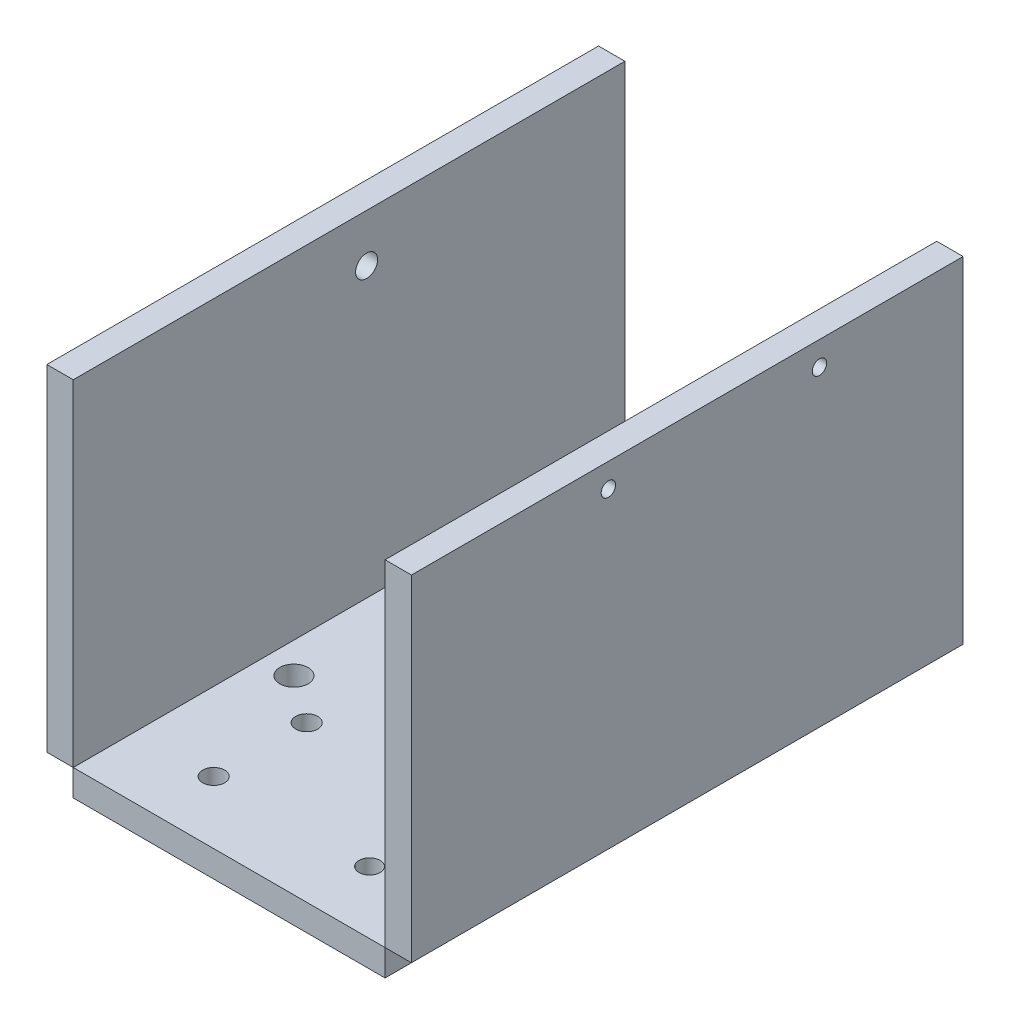
SolidWorks part; units mm, degrees
ref_plane "Alzado" through (0, 0, 0) normal (0, 0, 1) x (1, 0, 0)
ref_plane "Planta" through (0, 0, 0) normal (0, 1, 0) x (1, 0, 0)
ref_plane "Vista lateral" through (0, 0, 0) normal (1, 0, 0) x (0, 0, -1)
sketch "Croquis1" plane through (0, 0, 0) normal (0, 1, 0) x (1, 0, 0)
  line L0 (0, -12.4562) -> (32.5, -12.4562) construction
  line L1 (0, 0) -> (65, 0)
  line L2 (0, 0) -> (0, -115)
  line L3 (0, -115) -> (65, -115)
  line L4 (65, 0) -> (65, -115)
  line L5 (32.5, 0) -> (32.5, -12.4562) construction
  line L6 (32.5, -12.4562) -> (65, -12.4562) construction
  line L7 (48.75, -6.2281) -> (16.25, -6.2281) construction
  line L8 (16.25, -6.2281) -> (16.25, -12.4562) construction
  line L9 (16.25, -18.6843) -> (16.25, -82.5875) construction
  line L10 (16.25, -82.5875) -> (48.75, -82.5875) construction
  line L11 (16.25, -82.5875) -> (16.25, -92.2821) construction
  line L12 (16.25, -92.2821) -> (48.75, -92.2821) construction
  circle A0 centre (16.25, -6.2281) radius 2.3
  circle A1 centre (48.75, -6.2281) radius 2.3
  circle A2 centre (48.75, -18.6843) radius 2.3
  circle A3 centre (16.25, -18.6843) radius 2.3
  circle A4 centre (16.25, -82.5875) radius 2.3
  circle A5 centre (48.75, -82.5875) radius 2.2
  circle A6 centre (48.75, -101.9767) radius 2.2
  circle A7 centre (16.25, -101.9767) radius 2.3
  point P13 (32.5, -6.2281)
  dimension "D3" = 6.2281
  dimension "D1" = 65
  dimension "D2" = 115
extrude "Saliente-Extruir1" add sketch "Croquis1" along normal blind 5.5
sketch "Croquis2" plane through (0, 0, 0) normal (-1, 0, 0) x (0, 0, 1)
  line L1 (115, 5.5) -> (0, 5.5)
  line L2 (115, 5.5) -> (115, 75.5)
  line L3 (115, 75.5) -> (0, 75.5)
  line L4 (0, 5.5) -> (0, 75.5)
  dimension "D1" = 70
  dimension "D2" = 115
extrude "Saliente-Extruir2" add sketch "Croquis2" along normal blind 5.5 separate body
sketch "Croquis3" plane through (65, 0, 0) normal (1, 0, 0) x (0, 0, -1)
  line L1 (0, 5.5) -> (-115, 5.5)
  line L2 (0, 5.5) -> (0, 75.5)
  line L3 (0, 75.5) -> (-115, 75.5)
  line L4 (-115, 5.5) -> (-115, 75.5)
  dimension "D1" = 70
  dimension "D2" = 115
extrude "Saliente-Extruir3" add sketch "Croquis3" along normal blind 5.5 separate body
sketch "Croquis4" plane through (0, 5.5, 0) normal (0, 1, 0) x (1, 0, 0)
  circle A0 centre (55.6386, -75.4209) radius 3.1171
  circle A1 centre (6.4196, -75.4209) radius 2.9578
extrude "Cortar-Extruir1" cut sketch "Croquis4" against normal blind 5.5
sketch "Croquis5" plane through (-5.5, 0, 0) normal (-1, 0, 0) x (0, 0, 1)
  line L0 (53.8494, 65.5) -> (53.8494, 75.5) construction
  line L1 (115, 75.5) -> (0, 75.5) construction
  circle A1 centre (53.8494, 65.5) radius 2.3
extrude "Cortar-Extruir2" cut sketch "Croquis5" against normal blind 5.5
sketch "Croquis6" plane through (0, 5.5, 0) normal (0, 1, 0) x (1, 0, 0)
  line L0 (24.2647, -3.5726) -> (30.7647, -3.5726) construction
  line L1 (30.7647, -3.5726) -> (37.2647, -3.5726) construction
  circle A0 centre (24.2647, -3.5726) radius 1.627
  circle A1 centre (30.7647, -3.5726) radius 1.627
  circle A2 centre (37.2647, -3.5726) radius 1.627
extrude "Cortar-Extruir3" cut sketch "Croquis6" against normal blind 5.5
sketch "Croquis7" plane through (65, 0, 0) normal (-1, 0, 0) x (0, 0, 1)
  line L0 (29.9505, 70.5) -> (73.9505, 70.5) construction
  line L1 (29.9505, 70.5) -> (29.9505, 75.5) construction
  line L2 (0, 75.5) -> (115, 75.5) construction
  circle A0 centre (29.9505, 70.5) radius 1.5
  circle A1 centre (73.9505, 70.5) radius 1.5
  dimension "D1" = 3
  dimension "D2" = 3
extrude "Cortar-Extruir4" cut sketch "Croquis7" against normal blind 5.5
